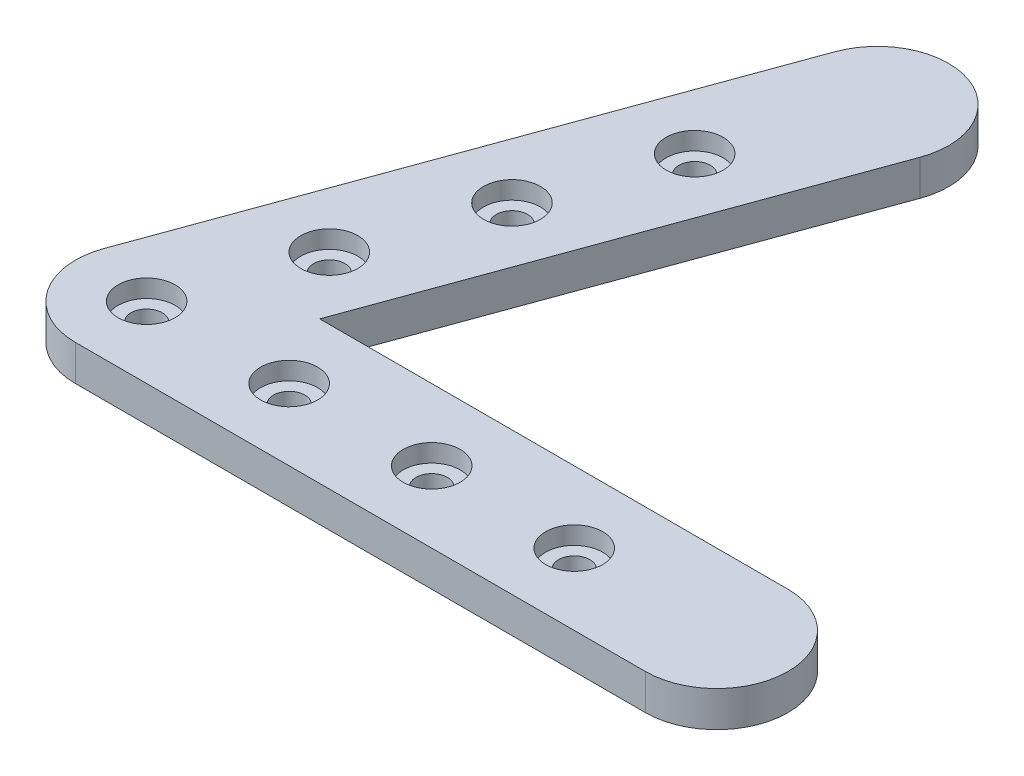
SolidWorks part; units mm, degrees
ref_plane "Front" through (0, 0, 0) normal (0, 0, 1) x (1, 0, 0)
ref_plane "Top" through (0, 0, 0) normal (0, 1, 0) x (1, 0, 0)
ref_plane "Right" through (0, 0, 0) normal (1, 0, 0) x (0, 0, -1)
sketch "Sketch5" plane through (0, 0, 0) normal (0, 1, 0) x (1, 0, 0)
  line L0 (0, 0) -> (101.6, 0) construction
  line L1 (0, 12.7) -> (101.6, 12.7)
  line L2 (0, -12.7) -> (101.6, -12.7)
  line L3 (0, 0) -> (34.7492, 95.4728) construction
  line L4 (-11.9341, 4.3437) -> (22.8152, 99.8164)
  line L5 (11.9341, -4.3437) -> (46.6833, 91.1291)
  line L12 (-11.9341, 4.3437) -> (22.8152, 99.8164)
  line L13 (46.6833, 91.1291) -> (18.1375, 12.7)
  arc A0 (0, 12.7) -> (0, -12.7) centre (0, 0) ccw
  arc A1 (101.6, -12.7) -> (101.6, 12.7) centre (101.6, 0) ccw
  arc A2 (-11.9341, 4.3437) -> (11.9341, -4.3437) centre (0, 0) ccw
  arc A3 (46.6833, 91.1291) -> (22.8152, 99.8164) centre (34.7492, 95.4728) ccw
  circle A6 centre (0, 0) radius 2.794
  point P3 (50.8, 0)
  point P8 (17.3746, 47.7364)
  dimension "D1" = 70
extrude "Boss-Extrude21" add sketch "Sketch5" along normal blind 6.35 contours A2 L2 A1 L1 L5 | L5 A3 L4 A0 L1 | A0 A2 L5 L1 A6
sketch "Sketch6" plane through (0, 0, 0) normal (0, -1, 0) x (-1, 0, 0)
  line L0 (11.9341, 4.3437) -> (-22.8152, 99.8164) construction
  line L1 (-18.1375, 12.7) -> (-46.6833, 91.1291) construction
  line L2 (11.9341, 4.3437) -> (-22.8152, 99.8164) construction
  circle A0 centre (-50.8, 0) radius 2.794
  circle A1 centre (-17.3746, 47.7364) radius 2.794
  circle A2 centre (0, 0) radius 2.794 construction
  circle A3 centre (0, 0) radius 2.794 construction
  circle A4 centre (-25.4, 0) radius 2.794
  circle A5 centre (-76.2, 0) radius 2.794
  circle A6 centre (-8.6873, 23.8682) radius 2.794
  circle A7 centre (-26.0619, 71.6046) radius 2.794
  dimension "D1" = 5.588
  dimension "D2" = 5.588
  dimension "D3" = 50.8
  dimension "D4" = 50.8
  dimension "D5" = 12.7
  dimension "D6" = 25.4
  dimension "D8" = 25.4
  dimension "D7" = 25.4
  dimension "D9" = 25.4
  dimension "D10" = 12.7
  dimension "D11" = 12.7
extrude "Cut-Extrude3" cut sketch "Sketch6" against normal blind 6.35
sketch "Sketch7" plane through (0, 6.35, 0) normal (0, 1, 0) x (1, 0, 0)
  circle A0 centre (26.0619, 71.6046) radius 5.08
  circle A1 centre (17.3746, 47.7364) radius 5.08
  circle A2 centre (8.6873, 23.8682) radius 5.08
  circle A3 centre (0, 0) radius 5.08
  circle A4 centre (25.4, 0) radius 5.08
  circle A5 centre (50.8, 0) radius 5.08
  circle A6 centre (76.2, 0) radius 5.08
extrude "Cut-Extrude4" cut sketch "Sketch7" against normal blind 3.175
